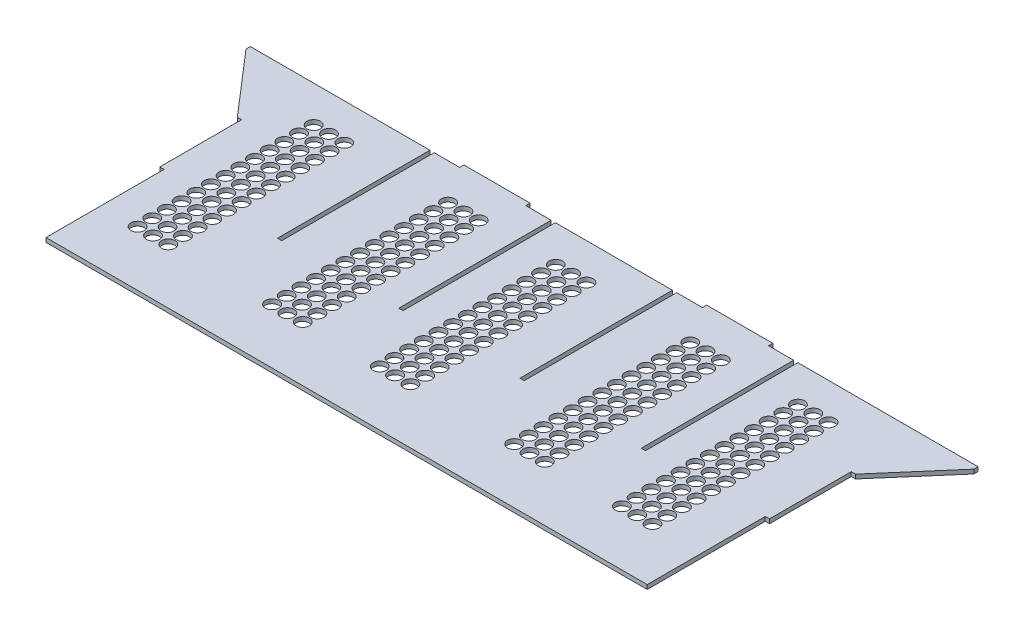
SolidWorks part; units mm, degrees
material "6061-T6 (SS)"
ref_plane "X-Y Datum" through (0, 0, 0) normal (0, 0, 1) x (1, 0, 0)
ref_plane "X-Z Datum" through (0, 0, 0) normal (0, 1, 0) x (1, 0, 0)
ref_plane "Y-Z Datum" through (0, 0, 0) normal (1, 0, 0) x (0, 0, -1)
sketch "Sketch1" plane through (0, 0, 0) normal (0, 0, 1) x (1, 0, 0)
  line L1 (-228.6115, -1.5875) -> (228.6115, -1.5875)
  line L2 (-228.6115, -1.5875) -> (-228.6115, 1.5875)
  line L3 (-228.6115, 1.5875) -> (228.6115, 1.5875)
  line L4 (228.6115, -1.5875) -> (228.6115, 1.5875)
  line L5 (-228.6115, -1.5875) -> (228.6115, 1.5875) construction
  line L6 (-228.6115, 1.5875) -> (228.6115, -1.5875) construction
  point P0 (0, 0)
  dimension "D1" = 3.175
  dimension "D2" = 457.223
extrude "Boss-Extrude1" add sketch "Sketch1" along normal blind 200.642
sketch "Sketch2" plane through (0, 1.5875, 0) normal (0, 1, 0) x (1, 0, 0)
  line L0 (228.6115, 0) -> (225.4365, 0)
  line L1 (228.6115, 0) -> (-228.6115, 0) construction
  line L2 (225.4365, 0) -> (137.8065, 0)
  line L3 (137.8065, 0) -> (134.6315, 0)
  line L10 (134.6315, 0) -> (137.8065, 0)
  line L11 (134.6315, 0) -> (134.6315, -114.3)
  line L12 (134.6315, -114.3) -> (137.8065, -114.3)
  line L13 (137.8065, 0) -> (137.8065, -114.3)
  line M2 (228.6115, 0) -> (-228.6115, 0)
  dimension "D1" = 87.63
  dimension "D2" = 3.175
  dimension "D3" = 114.3
  dimension "D4" = 3.175
extrude "Cut-Extrude1" cut sketch "Sketch2" against normal through all contours L13 L11 L12 M2
pattern_linear "LPattern1" count 4 spacing 90.932 along (-1, 0, 0) of "Cut-Extrude1"
sketch "Sketch3" plane through (0, 0, 0) normal (0, 0, -1) x (-1, 0, 0)
  line L0 (-66.1907, -1.5583) -> (-66.1907, -1.5875)
  line L9 (-46.8745, -1.5875) -> (-134.6315, -1.5875) construction
  line L11 (-134.6315, 1.5875) -> (-46.8745, 1.5875) construction
  line L12 (47.2325, 1.5875) -> (134.9895, 1.5875) construction
  line L13 (-66.1907, -1.5875) -> (-115.8495, -1.5875)
  line L14 (-66.1907, -1.5875) -> (-66.1907, 1.5875)
  line L15 (-66.1907, 1.5875) -> (-115.8495, 1.5875)
  line L16 (-115.8495, -1.5875) -> (-115.8495, 1.5875)
  line L17 (66.1907, -1.5875) -> (115.8495, -1.5875)
  line L18 (66.1907, -1.5875) -> (66.1907, 1.5875)
  line L19 (66.1907, 1.5875) -> (115.8495, 1.5875)
  line L20 (115.8495, -1.5875) -> (115.8495, 1.5875)
  dimension "D2" = 49.6588
sketch "Sketch4" plane through (0, -1.5875, 0) normal (0, -1, 0) x (1, 0, 0)
  line L0 (-228.6115, 0) -> (-272.8865, 0)
  line L2 (-228.6115, 200.642) -> (-228.6115, 0) construction
  line L3 (-228.6115, 50.8) -> (-228.6115, 0)
  line L4 (-272.8865, 0) -> (-272.8865, 3.175)
  line L6 (-228.6115, 50.8) -> (-231.7865, 50.8)
  line L7 (-272.8865, 3.175) -> (-231.7865, 50.8)
  dimension "D1" = 44.275
  dimension "D2" = 50.8
  dimension "D3" = 3.175
extrude "Boss-Extrude3" add sketch "Sketch4" against normal blind 3.175
mirror "Mirror1" about plane through (0, 0, 0) normal (1, 0, 0) of "Boss-Extrude3"
sketch "Sketch5" plane through (0, -1.5875, 0) normal (0, -1, 0) x (1, 0, 0)
  line L1 (-228.6115, 200.642) -> (-225.4365, 200.642)
  line L2 (-228.6115, 200.642) -> (-228.6115, 112.128)
  line L3 (-228.6115, 112.128) -> (-225.4365, 112.128)
  line L4 (-225.4365, 200.642) -> (-225.4365, 112.128)
  dimension "D1" = 3.175
  dimension "D2" = 88.514
extrude "Cut-Extrude2" cut sketch "Sketch5" against normal blind 3.175
mirror "Mirror2" about plane through (0, 0, 0) normal (1, 0, 0) of "Cut-Extrude2"
extrude "Boss-Extrude4" add sketch "Sketch3" along normal blind 3.18
sketch "Sketch6" plane through (0, -1.5875, 0) normal (0, -1, 0) x (1, 0, 0)
  circle A0 centre (-175.1185, 159.2567) radius 5 construction
  circle A1 centre (-186.6185, 159.2567) radius 5 construction
  circle A2 centre (-198.1185, 159.2567) radius 5 construction
  circle A3 centre (-175.1185, 159.2567) radius 5
  circle A4 centre (-186.6185, 159.2567) radius 5
  circle A5 centre (-198.1185, 159.2567) radius 5
extrude "Cut-Extrude3" cut sketch "Sketch6" against normal through all
pattern_linear "LPattern2" count 13 spacing 11 along (0, 0, -1) of "Cut-Extrude3"
sketch "Sketch7" plane through (0, -1.5875, 0) normal (0, -1, 0) x (1, 0, 0)
  line L38 (228.6115, 112.128) -> (225.4365, 112.128)
  line L39 (225.4365, 112.128) -> (225.4365, 200.642)
  line L40 (225.4365, 200.642) -> (-225.4365, 200.642)
  line L41 (-225.4365, 200.642) -> (-225.4365, 112.128)
  line L42 (-225.4365, 112.128) -> (-228.6115, 112.128)
  line L43 (-228.6115, 112.128) -> (-228.6115, 50.8)
  line L44 (-228.6115, 50.8) -> (-231.7865, 50.8)
  line L45 (-231.7865, 50.8) -> (-272.8865, 3.175)
  line L46 (-272.8865, 3.175) -> (-272.8865, 0)
  line L47 (-272.8865, 0) -> (-138.1645, 0)
  line L48 (-138.1645, 0) -> (-138.1645, 114.3)
  line L49 (-138.1645, 114.3) -> (-134.9895, 114.3)
  line L50 (-134.9895, 114.3) -> (-134.9895, 0)
  line L51 (-134.9895, 0) -> (-115.8495, 0)
  line L52 (-115.8495, 0) -> (-115.8495, -3.18)
  line L53 (-115.8495, -3.18) -> (-66.1907, -3.18)
  line L54 (-66.1907, -3.18) -> (-66.1907, 0)
  line L55 (-66.1907, 0) -> (-47.2325, 0)
  line L56 (-47.2325, 0) -> (-47.2325, 114.3)
  line L57 (-47.2325, 114.3) -> (-44.0575, 114.3)
  line L58 (-44.0575, 114.3) -> (-44.0575, 0)
  line L59 (-44.0575, 0) -> (43.6995, 0)
  line L60 (43.6995, 0) -> (43.6995, 114.3)
  line L61 (43.6995, 114.3) -> (46.8745, 114.3)
  line L62 (46.8745, 114.3) -> (46.8745, 0)
  line L63 (46.8745, 0) -> (66.1907, 0)
  line L64 (66.1907, 0) -> (66.1907, -3.18)
  line L65 (66.1907, -3.18) -> (115.8495, -3.18)
  line L66 (115.8495, -3.18) -> (115.8495, 0)
  line L67 (115.8495, 0) -> (134.6315, 0)
  line L68 (134.6315, 0) -> (134.6315, 114.3)
  line L69 (134.6315, 114.3) -> (137.8065, 114.3)
  line L70 (137.8065, 114.3) -> (137.8065, 0)
  line L71 (137.8065, 0) -> (272.8865, 0)
  line L72 (272.8865, 0) -> (272.8865, 3.175)
  line L73 (272.8865, 3.175) -> (231.7865, 50.8)
  line L74 (231.7865, 50.8) -> (228.6115, 50.8)
  line L75 (228.6115, 50.8) -> (228.6115, 112.128)
  line L76 (228.6115, 112.128) -> (225.4365, 112.128)
  line L77 (225.4365, 112.128) -> (225.4365, 200.642)
  line L78 (225.4365, 200.642) -> (-225.4365, 200.642)
  line L79 (-225.4365, 200.642) -> (-225.4365, 112.128)
  line L80 (-225.4365, 112.128) -> (-228.6115, 112.128)
  line L81 (-228.6115, 112.128) -> (-228.6115, 50.8)
  line L82 (-228.6115, 50.8) -> (-231.7865, 50.8)
  line L83 (-231.7865, 50.8) -> (-272.8865, 3.175)
  line L84 (-272.8865, 3.175) -> (-272.8865, 0)
  line L85 (-272.8865, 0) -> (-138.1645, 0)
  line L86 (-138.1645, 0) -> (-138.1645, 114.3)
  line L87 (-138.1645, 114.3) -> (-134.9895, 114.3)
  line L88 (-134.9895, 114.3) -> (-134.9895, 0)
  line L89 (-134.9895, 0) -> (-115.8495, 0)
  line L90 (-115.8495, 0) -> (-115.8495, -3.18)
  line L91 (-115.8495, -3.18) -> (-66.1907, -3.18)
  line L92 (-66.1907, -3.18) -> (-66.1907, 0)
  line L93 (-66.1907, 0) -> (-47.2325, 0)
  line L94 (-47.2325, 0) -> (-47.2325, 114.3)
  line L95 (-47.2325, 114.3) -> (-44.0575, 114.3)
  line L96 (-44.0575, 114.3) -> (-44.0575, 0)
  line L97 (-44.0575, 0) -> (43.6995, 0)
  line L98 (43.6995, 0) -> (43.6995, 114.3)
  line L99 (43.6995, 114.3) -> (46.8745, 114.3)
  line L100 (46.8745, 114.3) -> (46.8745, 0)
  line L101 (46.8745, 0) -> (66.1907, 0)
  line L102 (66.1907, 0) -> (66.1907, -3.18)
  line L103 (66.1907, -3.18) -> (115.8495, -3.18)
  line L104 (115.8495, -3.18) -> (115.8495, 0)
  line L105 (115.8495, 0) -> (134.6315, 0)
  line L106 (134.6315, 0) -> (134.6315, 114.3)
  line L107 (134.6315, 114.3) -> (137.8065, 114.3)
  line L108 (137.8065, 114.3) -> (137.8065, 0)
  line L109 (137.8065, 0) -> (272.8865, 0)
  line L110 (272.8865, 0) -> (272.8865, 3.175)
  line L111 (272.8865, 3.175) -> (231.7865, 50.8)
  line L112 (231.7865, 50.8) -> (228.6115, 50.8)
  line L113 (228.6115, 50.8) -> (228.6115, 112.128)
  circle A0 centre (-16.5045, 159.2567) radius 5 construction
  circle A1 centre (-16.5045, 159.2567) radius 5
  dimension "D1" = 0
pattern_linear "LPattern3" count 3 spacing 181.6 along (1, 0, 0) of "LPattern2", "Cut-Extrude3"
sketch "Sketch9" plane through (0, -1.5875, 0) normal (0, -1, 0) x (1, 0, 0)
  circle A6 centre (-74.3095, 159.2567) radius 5 construction
  circle A7 centre (-85.8095, 159.2567) radius 5 construction
  circle A8 centre (-97.3095, 159.2567) radius 5 construction
  circle A9 centre (-74.3095, 159.2567) radius 5
  circle A10 centre (-85.8095, 159.2567) radius 5
  circle A11 centre (-97.3095, 159.2567) radius 5
extrude "Cut-Extrude4" cut sketch "Sketch9" against normal through all
pattern_linear "LPattern5" count 13 spacing 11 along (0, 0, -1) of "Cut-Extrude4"
pattern_linear "LPattern6" count 2 spacing 181.6 along (1, 0, 0) of "LPattern5", "Cut-Extrude4"
